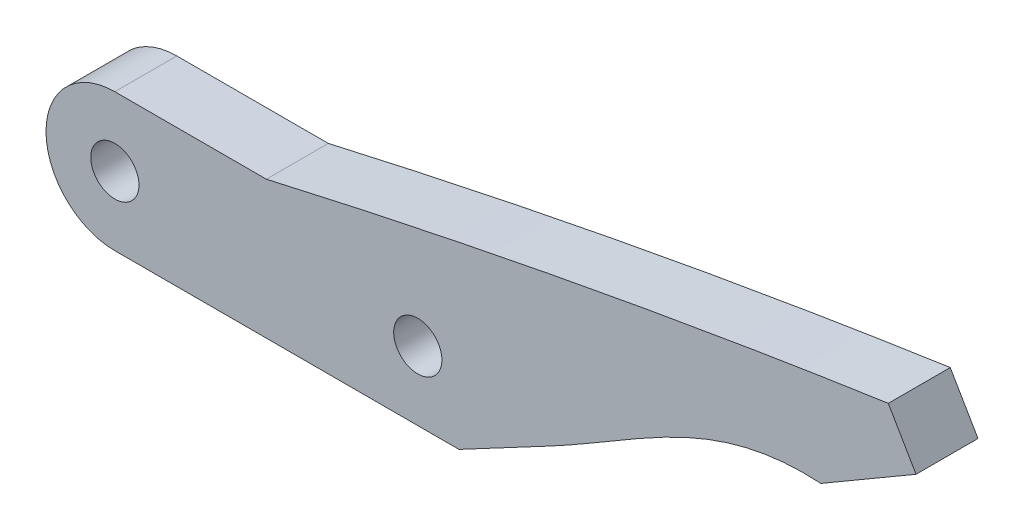
SolidWorks part; units mm, degrees
ref_plane "Front Plane" through (0, 0, 0) normal (0, 0, 1) x (1, 0, 0)
ref_plane "Top Plane" through (0, 0, 0) normal (0, 1, 0) x (1, 0, 0)
ref_plane "Right Plane" through (0, 0, 0) normal (1, 0, 0) x (0, 0, -1)
sketch "Sketch1" plane through (0, 0, 0) normal (0, 0, 1) x (1, 0, 0)
  line L0 (-11, 0) -> (11, 0)
  line L1 (0, 0) -> (0, 2.7219) construction
  line L3 (-18.5514, -5) -> (18.5514, -5)
  line L4 (-18.5514, -5) -> (-18.5514, 5)
  line L5 (-18.5514, 5) -> (18.5514, 5)
  line L6 (18.5514, -5) -> (18.5514, 5)
  line L7 (-18.5514, -5) -> (18.5514, 5) construction
  line L8 (-18.5514, 5) -> (18.5514, -5) construction
  circle A0 centre (-11, 0) radius 1.75
  circle A1 centre (-11, 0) radius 5
  circle A2 centre (11, 0) radius 1.75
  circle A3 centre (11, 0) radius 5
  point P4 (0, 0)
  dimension "D2" = 10
  dimension "D3" = 3.5
  dimension "D1" = 22
extrude "Boss-Extrude1" add sketch "Sketch1" along normal blind 4.5
sketch "Sketch2" plane through (0, 0, 4.5) normal (0, 0, 1) x (1, 0, 0)
  line L0 (45.1672, 13.4854) -> (47.1822, 10.03)
  line L1 (47.1822, 10.03) -> (40.2714, 6)
  line L2 (-11, -5) -> (11, -5) construction
  line L3 (11, 0) -> (11, -5) construction
  line L4 (20.61, -1.48) -> (13.99, -5)
  line L5 (11, -5) -> (13.99, -5)
  line L6 (-11, 5) -> (11, 5) construction
  line L7 (0, 5) -> (11, 5)
  arc A0 (11, -5) -> (11, 5) centre (11, 0) ccw construction
  arc A1 (11, -5) -> (11, 5) centre (11, 0) ccw
  spline S0 degree 3 poles (40.2714, 6) (32.4193, 6.4877) (27.1719, 2.0091) (20.61, -1.48) knots 0 0 0 0 1 1 1 1
  spline S1 degree 2 poles (0, 5) (22.4156, 10.1456) (45.1672, 13.4854) knots 0 0 0 1 1 1
  arc M5 (11, -5) -> (11, 5) centre (11, 0) ccw
  line M6 (11, 5) -> (-11, 5)
  dimension "D11" = 13.52
  dimension "D1" = 4
  dimension "D2" = 8
  dimension "D3" = 11
  dimension "D4" = 15.03
  dimension "D5" = 18.4854
  dimension "D6" = 9.45
  dimension "D7" = 3.52
  dimension "D8" = 20.52
  dimension "9.61" = 9.61
  dimension "D9" = 31.27
  dimension "D10" = 2.99
  dimension "D12" = 15.07
extrude "Boss-Extrude2" add sketch "Sketch2" against normal up to surface (4.5 mm away) contours S1 L5 L4 S0 L1 L0 M6 M5 up to face at (0, 0, 0)
